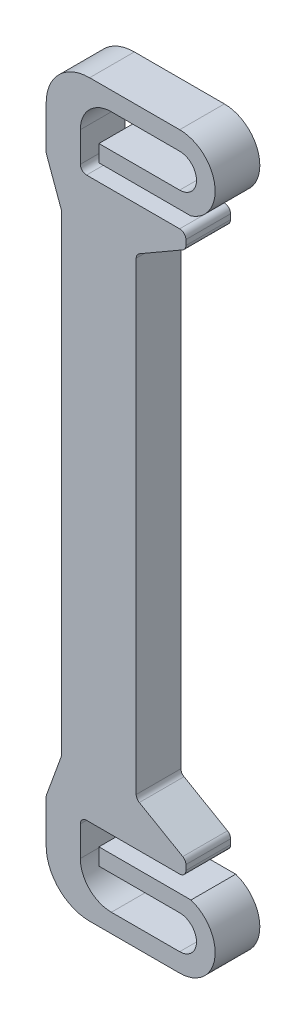
SolidWorks part; units mm, degrees
ref_plane "Front Plane" through (0, 0, 0) normal (0, 0, 1) x (1, 0, 0)
ref_plane "Top Plane" through (0, 0, 0) normal (0, 1, 0) x (1, 0, 0)
ref_plane "Right Plane" through (0, 0, 0) normal (1, 0, 0) x (0, 0, -1)
sketch "Sketch1" plane through (0, 0, 0) normal (0, 0, 1) x (1, 0, 0)
  line L10 (-3, 18.8893) -> (-3, 0)
  line L11 (-3, 0) -> (0, 0)
  line L12 (0, 0) -> (3, 0)
  line L13 (3, 0) -> (3, 18.7019)
  line L16 (3.25, 19.1349) -> (6.75, 21.1557)
  line L18 (-4.25, 23.85) -> (13.2067, 23.85) construction
  line L19 (7, 21.5887) -> (7, 22)
  line L20 (165, 22.5) -> (0, 22.5) construction
  line L21 (6.5, 22.5) -> (-1, 22.5)
  line L27 (0, 23.7) -> (6.5, 23.7)
  line L32 (-0.75, 29.4118) -> (6.5, 29.4118)
  line L46 (-3.0302, 19.0603) -> (-4.2198, 22.329)
  line L47 (-4.25, 22.5) -> (-4.25, 25.9118)
  line L74 (0, 23.7) -> (0, 25.2)
  line L75 (0, 25.2) -> (6.5, 25.2)
  line L77 (6.5, 27.9118) -> (1, 27.9118)
  line L78 (-1.5, 25.4118) -> (-1.5, 23)
  line L79 (-1, 22.5) -> (-4.25, 22.5)
  line L80 (6.5, 23.7) -> (6.5, 22.5)
  arc A11 (7, 22) -> (6.5, 22.5) centre (6.5, 22) ccw
  arc A16 (3, 18.7019) -> (3.25, 19.1349) centre (3.5, 18.7019) cw
  arc A17 (6.75, 21.1557) -> (7, 21.5887) centre (6.5, 21.5887) ccw
  arc A35 (-3.0302, 19.0603) -> (-3, 18.8893) centre (-3.5, 18.8893) cw
  arc A36 (-4.2198, 22.329) -> (-4.25, 22.5) centre (-3.75, 22.5) cw
  arc A58 (6.5, 23.7) -> (6.5, 29.4118) centre (6.5, 26.5559) ccw
  arc A59 (6.5, 25.2) -> (6.5, 27.9118) centre (6.5, 26.5559) ccw
  arc A60 (-0.75, 29.4118) -> (-4.25, 25.9118) centre (-0.75, 25.9118) ccw
  arc A61 (-1.5, 25.4118) -> (1, 27.9118) centre (1, 25.4118) cw
  arc A62 (-1.5, 23) -> (-1, 22.5) centre (-1, 23) ccw
  point P1 (-0.6275, 25.5394)
  point P3 (-1.061, 29.4118)
  point P51 (7, 21.3)
  point P57 (7, 22.5)
  point P114 (-4.25, 22.4118)
  dimension "D20" = 0.5
  dimension "D28" = 0.5
  dimension "D12" = 0.5
  dimension "D17" = 0.5
  dimension "D19" = 2.5
  dimension "D16" = 3.5
  dimension "D5" = 6
  dimension "D4" = 4
  dimension "D6" = 1.2
  dimension "D7" = 120
  dimension "D8" = 1.35
  dimension "D24" = 20
  dimension "D27" = 7
  dimension "D3" = 1.2
  dimension "D10" = 3
  dimension "D11" = 1.5
  dimension "D13" = 2.75
  dimension "D15" = 1.5
  dimension "D18" = 8
  dimension "D9" = 1.5
  dimension "D14" = 22.5
extrude "Boss-Extrude1" add sketch "Sketch1" along normal mid plane 3.6 contours A36 L46 A35 L10 L11 L12 L13 A16 L16 A17 L19 A11 L21 L79 | L18 L47 L79 A62 L78 | L47 L18 L78 A61 L77 A59 L75 L74 A58 L32 A60
mirror "Mirror1" about plane through (0, 0, 0) normal (0, 1, 0) of bodies 101
equation "\"D10@Sketch1\"=\"D5@Sketch1\"/2"
equation "\"D15@Sketch1\"=\"D11@Sketch1\""
equation "\"D9@Sketch1\"=\"D11@Sketch1\""
